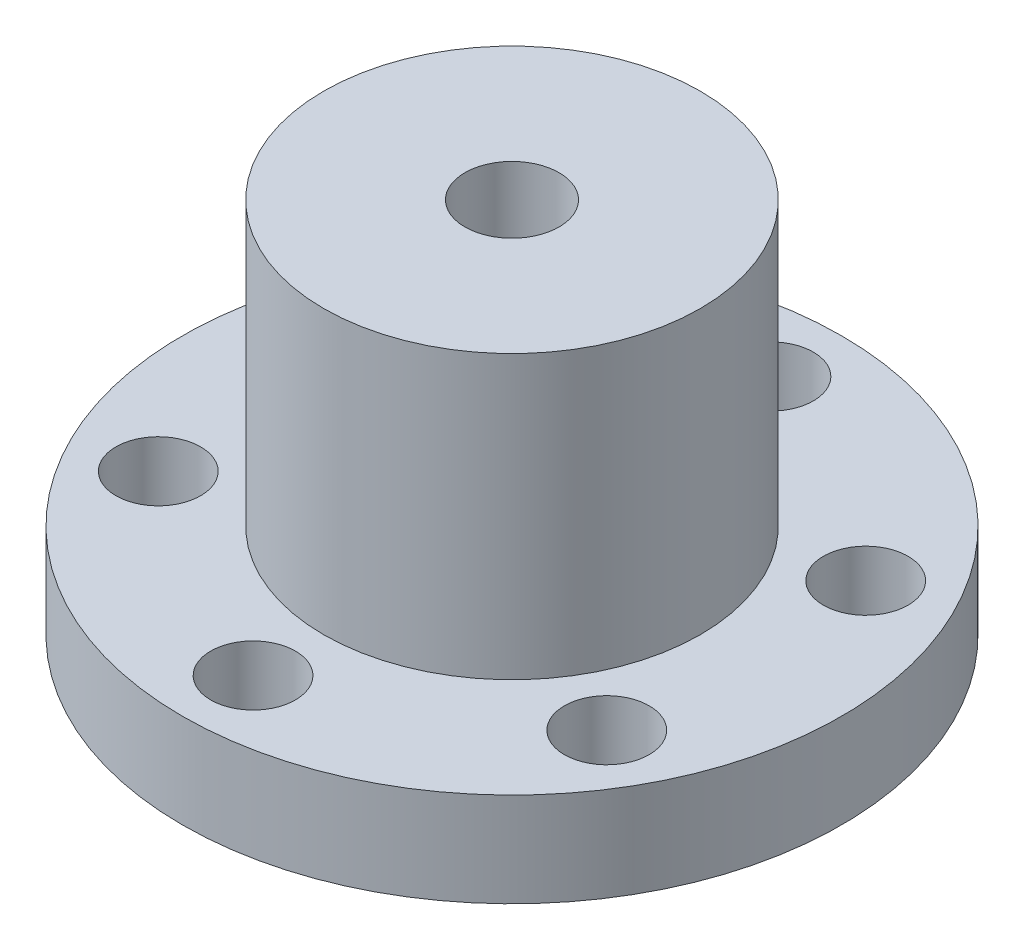
SolidWorks part; units mm, degrees
material "6061 Alloy"
ref_plane "Front Plane" through (0, 0, 0) normal (0, 0, 1) x (1, 0, 0)
ref_plane "Top Plane" through (0, 0, 0) normal (0, 1, 0) x (1, 0, 0)
ref_plane "Right Plane" through (0, 0, 0) normal (1, 0, 0) x (0, 0, -1)
sketch "Sketch2" plane through (0, 0, 0) normal (0, 1, 0) x (1, 0, 0)
  circle A0 centre (0, 0) radius 17.5
  circle A1 centre (0, 0) radius 13.75 construction
  circle A2 centre (0, 13.75) radius 2.25
  circle A3 centre (11.9078, 6.875) radius 2.25
  circle A4 centre (11.9078, -6.875) radius 2.25
  circle A5 centre (0, -13.75) radius 2.25
  circle A6 centre (-11.9078, -6.875) radius 2.25
  circle A7 centre (-11.9078, 6.875) radius 2.25
  point P18 (0, 0)
  dimension "D1" = 35
  dimension "D2" = 27.5
  dimension "D3" = 4.5
  dimension "D4" = 6
extrude "Boss-Extrude1" add sketch "Sketch2" along normal blind 5
sketch "Sketch3" plane through (0, 5, 0) normal (0, 1, 0) x (1, 0, 0)
  circle A0 centre (0, 0) radius 10
  dimension "D1" = 20
extrude "Boss-Extrude2" add sketch "Sketch3" along normal blind 15
sketch "Sketch4" plane through (0, 20, 0) normal (0, 1, 0) x (1, 0, 0)
  circle A0 centre (0, 0) radius 2.5
  dimension "D1" = 5
extrude "Cut-Extrude1" cut sketch "Sketch4" against normal through all
